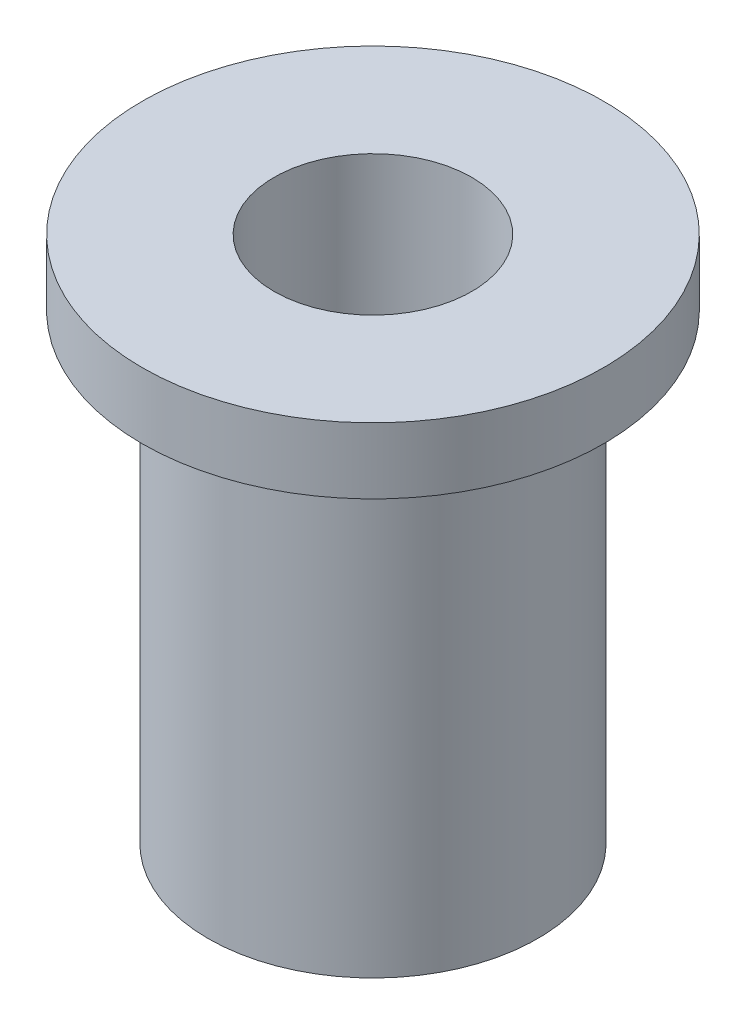
SolidWorks part; units mm, degrees
material "Brass"
ref_plane "Front Plane" through (0, 0, 0) normal (0, 0, 1) x (1, 0, 0)
ref_plane "Top Plane" through (0, 0, 0) normal (0, 1, 0) x (1, 0, 0)
ref_plane "Right Plane" through (0, 0, 0) normal (1, 0, 0) x (0, 0, -1)
sketch "Sketch1" plane through (0, 0, 0) normal (0, 1, 0) x (1, 0, 0)
  circle A0 centre (0, 0) radius 3.9688
  circle A1 centre (0, 0) radius 2.3813
extrude "Boss-Extrude1" add sketch "Sketch1" along normal blind 12.7
sketch "Sketch2" plane through (0, 12.7, 0) normal (0, 1, 0) x (1, 0, 0)
  circle A0 centre (0, 0) radius 5.5562
  circle A1 centre (0, 0) radius 2.3813
extrude "Boss-Extrude2" add sketch "Sketch2" against normal blind 1.5875
